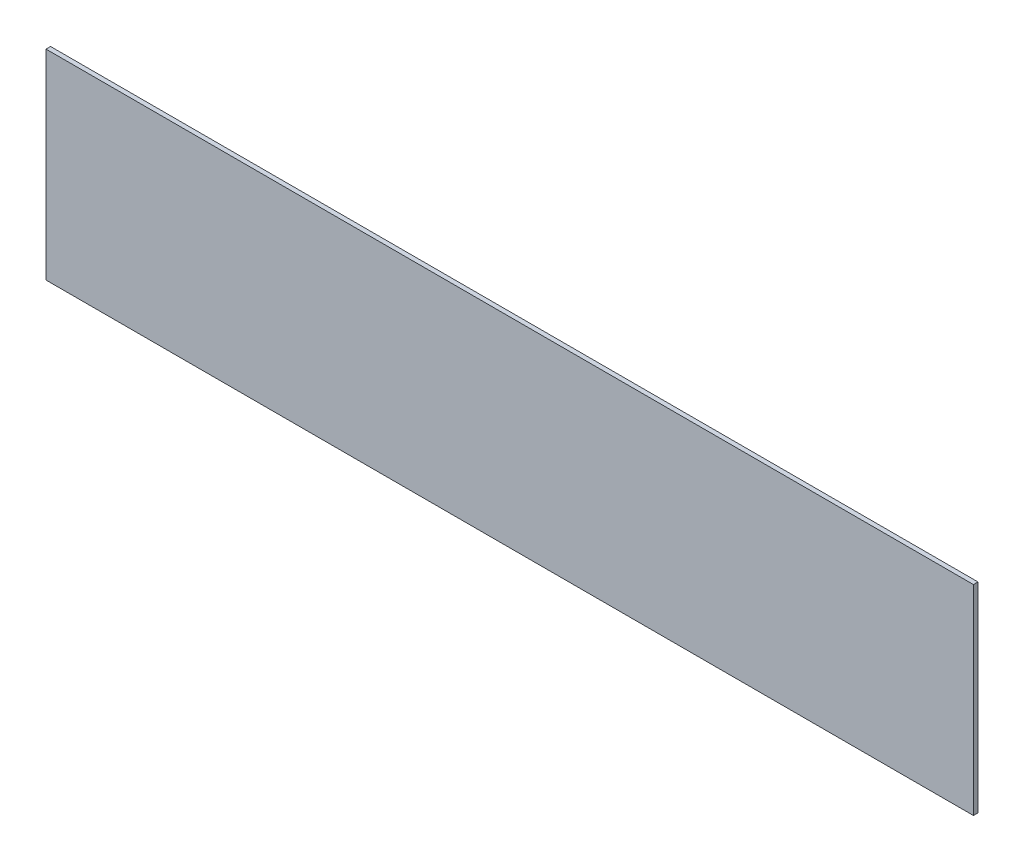
SolidWorks part; units mm, degrees
ref_plane "Front Plane" through (0, 0, 0) normal (0, 0, 1) x (1, 0, 0)
ref_plane "Top Plane" through (0, 0, 0) normal (0, 1, 0) x (1, 0, 0)
ref_plane "Right Plane" through (0, 0, 0) normal (1, 0, 0) x (0, 0, -1)
sketch "Sketch1" plane through (0, 0, 0) normal (0, 0, 1) x (1, 0, 0)
  line L1 (-1020, -220) -> (1020, -220)
  line L2 (-1020, -220) -> (-1020, 220)
  line L3 (-1020, 220) -> (1020, 220)
  line L4 (1020, -220) -> (1020, 220)
  line L5 (-1020, -220) -> (1020, 220) construction
  line L6 (-1020, 220) -> (1020, -220) construction
  point P0 (0, 0)
  dimension "D1" = 2040
  dimension "D2" = 440
extrude "Boss-Extrude1" add sketch "Sketch1" along normal blind 10
